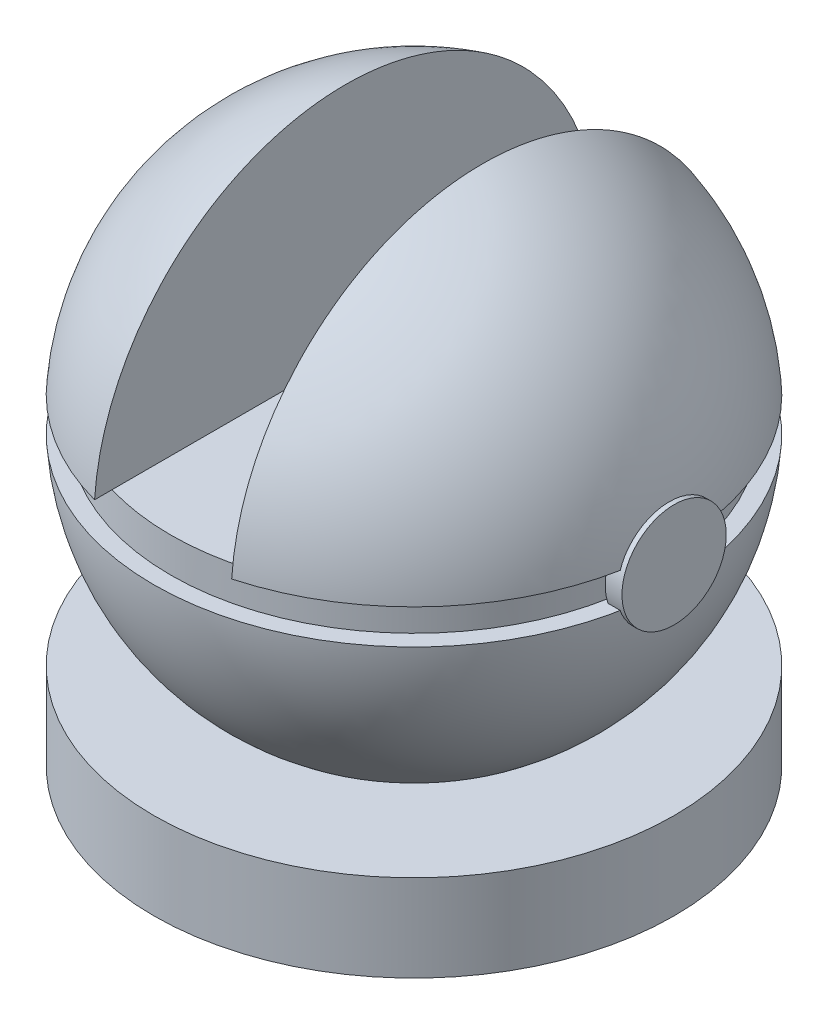
SolidWorks part; units mm, degrees
ref_plane "Front Plane" through (0, 0, 0) normal (0, 0, 1) x (1, 0, 0)
ref_plane "Top Plane" through (0, 0, 0) normal (0, 1, 0) x (1, 0, 0)
ref_plane "Right Plane" through (0, 0, 0) normal (1, 0, 0) x (0, 0, -1)
sketch "Sketch1" plane through (0, 0, 0) normal (0, 0, 1) x (1, 0, 0)
  line L0 (0, 38.1) -> (0, -38.1)
  line L1 (-35.56, 2.54) -> (-38.0152, 2.54)
  line L2 (-35.56, -2.54) -> (-38.0152, -2.54)
  line L3 (-35.56, 2.54) -> (-35.56, -2.54)
  arc A0 (0, 38.1) -> (-38.0152, 2.54) centre (0, 0) ccw
  arc A1 (-38.0152, -2.54) -> (0, -38.1) centre (0, 0) ccw
  dimension "D1" = 76.2
  dimension "D2" = 5.08
revolve "Revolve1" add sketch "Sketch1" angle 360 about L0
ref_plane "Plane1" through (35.56, 0, 0) normal (1, 0, 0) x (0, 0, -1)
sketch "Sketch4" plane through (35.56, 0, 0) normal (1, 0, 0) x (0, 0, -1)
  circle A0 centre (0, 0) radius 7.62
extrude "Boss-Extrude3" add sketch "Sketch4" along normal through all separate body
sketch "Sketch5" plane through (0, 0, 0) normal (0, 0, 1) x (1, 0, 0)
  line L0 (0, 0) -> (0, 38.1) construction
  line L1 (-10.0203, 38.1) -> (10.0203, 38.1)
  line L2 (-10.0203, 38.1) -> (-10.0203, 2.54)
  line L3 (-35.56, 2.54) -> (35.56, 2.54) construction
  line L4 (-10.0203, 2.54) -> (10.0203, 2.54)
  line L5 (10.0203, 2.54) -> (10.0203, 38.1)
  arc A0 (38.0152, 2.54) -> (-38.0152, 2.54) centre (0, 0) ccw construction
  point P8 (0, 38.1)
  dimension "D1" = 38.1
  dimension "D2" = 20.0406
extrude "Cut-Extrude1" cut sketch "Sketch5" against normal through all and the other way through all
ref_plane "Plane2" through (0, -38.1, 0) normal (0, -1, 0) x (-1, 0, 0)
sketch "Sketch6" plane through (0, -38.1, 0) normal (0, -1, 0) x (-1, 0, 0)
  circle A0 centre (0, 0) radius 38.0152
extrude "Boss-Extrude4" add sketch "Sketch6" along normal blind 6.35 and the other way blind 6.35 separate body contours A0
